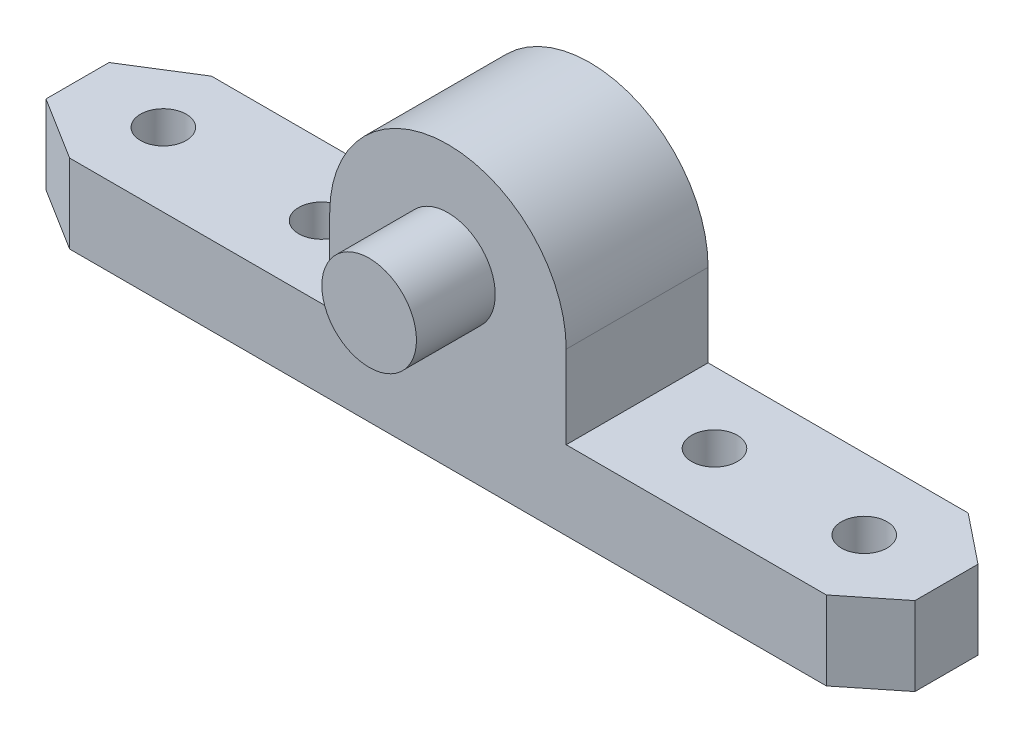
SolidWorks part; units mm, degrees
ref_plane "Płaszczyzna przednia" through (0, 0, 0) normal (0, 0, 1) x (1, 0, 0)
ref_plane "Płaszczyzna górna" through (0, 0, 0) normal (0, 1, 0) x (1, 0, 0)
ref_plane "Płaszczyzna prawa" through (0, 0, 0) normal (1, 0, 0) x (0, 0, -1)
sketch "Szkic1" plane through (0, 0, 0) normal (0, 1, 0) x (1, 0, 0)
  line L0 (24, 4.5) -> (27.1225, 2)
  line L1 (27.1225, 2) -> (27.1225, -2)
  line L2 (-24, -4.5) -> (24, -4.5)
  line L4 (-24, 4.5) -> (24, 4.5)
  line L6 (-24, -4.5) -> (24, 4.5) construction
  line L7 (-24, 4.5) -> (24, -4.5) construction
  line L8 (27.1225, -2) -> (24, -4.5)
  line L9 (-24, 4.5) -> (-28, 2)
  line L10 (-28, 2) -> (-28, -2)
  line L11 (-28, -2) -> (-24, -4.5)
  point P1 (0, 0)
  dimension "D3" = 4
  dimension "D1" = 48
  dimension "D2" = 9
  dimension "D4" = 4
  dimension "D5" = 4
  dimension "D6" = 4
  dimension "D7" = 4
  dimension "D8" = 4
extrude "Dodanie-wyciągnięcie1" add sketch "Szkic1" along normal blind 5
sketch "Szkic2" plane through (0, 0, 4.5) normal (0, 0, 1) x (1, 0, 0)
  line L0 (-24, 5) -> (24, 5) construction
  line L1 (-7.5, 5) -> (7.5, 5)
  line L2 (-7.5, 5) -> (-7.5, 10.25)
  line L4 (7.5, 10.25) -> (7.5, 5)
  arc A0 (-7.5, 10.25) -> (7.5, 10.25) centre (0, 10.25) cw
  point P7 (0, 5)
  dimension "D3" = 7.5
  dimension "D1" = 15
  dimension "D2" = 5.25
extrude "Dodanie-wyciągnięcie2" add sketch "Szkic2" against normal blind 9
sketch "Szkic3" plane through (0, 0, 4.5) normal (0, 0, 1) x (1, 0, 0)
  line L0 (0, 0) -> (0, 11) construction
  line L1 (-24, 0) -> (24, 0) construction
  circle A0 centre (0, 11) radius 3
  dimension "D2" = 6
  dimension "D1" = 11
sketch "Szkic4" plane through (0, 5, 0) normal (0, 1, 0) x (1, 0, 0)
  line L0 (27.1225, 0) -> (7.5, 0) construction
  line L1 (27.1225, -2) -> (27.1225, 2) construction
  line L2 (7.5, 4.5) -> (7.5, -4.5) construction
  line L3 (7.5, 0) -> (17.3112, 0) construction
  line L4 (17.3112, 0) -> (12.4056, 0) construction
  line L5 (12.4056, 0) -> (21.9056, 0) construction
  line L6 (-27.7881, 0.2121) -> (-7.5, 0) construction
  line L7 (-7.5, 4.5) -> (-7.5, -4.5) construction
  line L8 (-7.5, 0) -> (-17.644, 0.1061) construction
  line L9 (-17.644, 0.1061) -> (-12.572, 0.053) construction
  line L10 (-27.7881, 0.2121) -> (-17.644, 0.1061) construction
  line L11 (-17.644, 0.1061) -> (-22.716, 0.1591) construction
  circle A0 centre (12.4056, 0) radius 1.45
  circle A1 centre (21.9056, 0) radius 1.45
  circle A2 centre (-12.572, 0.053) radius 1.45
  circle A3 centre (-22.716, 0.1591) radius 1.45
  dimension "D1" = 2.9
  dimension "D3" = 2.9
  dimension "D4" = 2.9
  dimension "D5" = 2.9
  dimension "D2" = 9.5
extrude "Wytnij-wyciągnięcie1" cut sketch "Szkic4" against normal blind 6
extrude "Dodanie-wyciągnięcie3" add sketch "Szkic3" along normal blind 5
